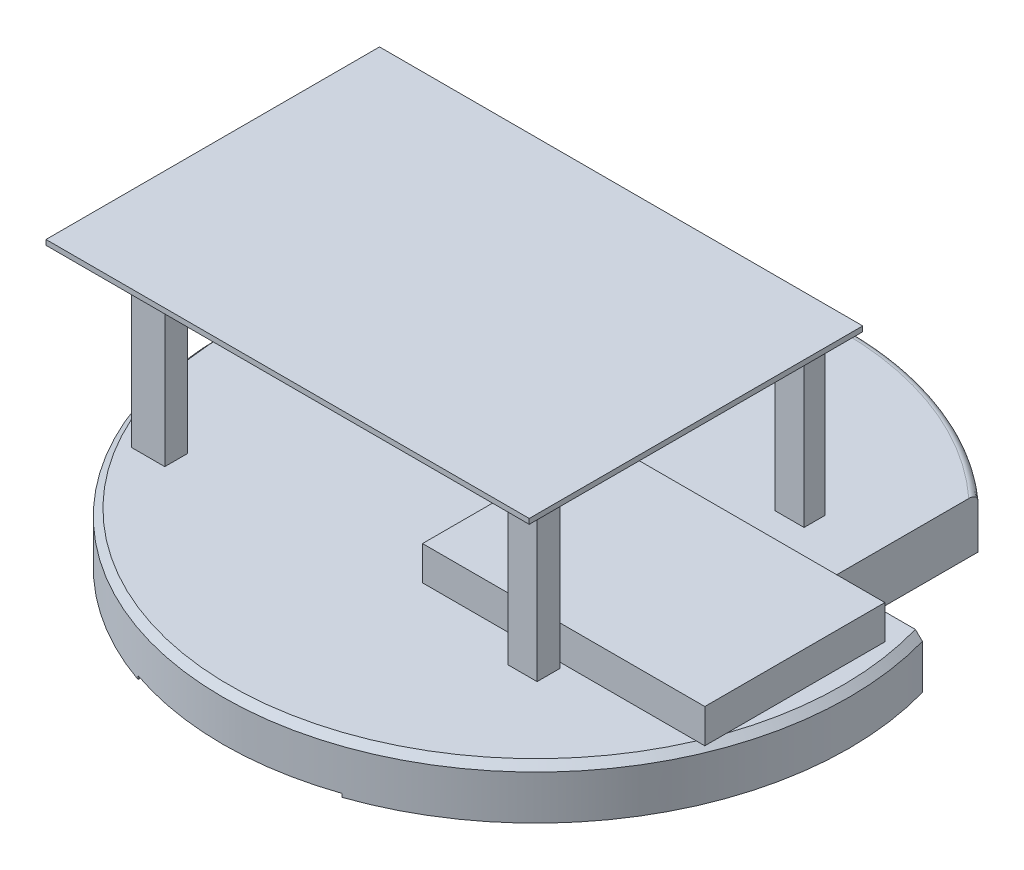
SolidWorks part; units mm, degrees
ref_plane "前视基准面" through (0, 0, 0) normal (0, 0, 1) x (1, 0, 0)
ref_plane "上视基准面" through (0, 0, 0) normal (0, 1, 0) x (1, 0, 0)
ref_plane "右视基准面" through (0, 0, 0) normal (1, 0, 0) x (0, 0, -1)
sketch "草图1" plane through (0, 0, 0) normal (0, 1, 0) x (1, 0, 0)
  line L0 (61, 68.8694) -> (61, 25)
  line L1 (0, 0) -> (0, 6.6219) construction
  line L2 (0, 0) -> (0, 25) construction
  line L3 (61, 25) -> (88.5381, 25)
  line L4 (-61, 25) -> (-88.5381, 25)
  line L5 (-61, 68.8694) -> (-61, 25)
  arc A0 (61, 68.8694) -> (-61, 68.8694) centre (0, 0) ccw
  arc A1 (-88.5381, 25) -> (88.5381, 25) centre (0, 0) ccw
  dimension "D1" = 184
  dimension "D2" = 61
  dimension "D3" = 25
extrude "凸台-拉伸1" add sketch "草图1" along normal blind 15
sketch "草图2" plane through (0, 0, 0) normal (0, -1, 0) x (1, 0, 0)
  line L0 (0, 100.028) -> (0, 25.3301) construction
  line L2 (-30, 49.7832) -> (-30, 92.7832)
  line L3 (-30, 49.7832) -> (30, 49.7832)
  line L4 (30, 49.7832) -> (30, 92.7832)
  line L5 (-30, 92.7832) -> (30, 92.7832)
  line L6 (-30, 49.7832) -> (30, 92.7832) construction
  line L7 (30, 49.7832) -> (-30, 92.7832) construction
  point P3 (0, 71.2832)
  dimension "D1" = 60
  dimension "D2" = 43
extrude "切除-拉伸1" cut sketch "草图2" against normal blind 1
sketch "草图3" plane through (0, 15, 0) normal (0, 1, 0) x (1, 0, 0)
  line L0 (88.5381, 25) -> (61, 25) construction
  line L1 (-93, 47) -> (49, 47)
  line L2 (-93, 47) -> (-93, -51)
  line L3 (-93, -51) -> (49, -51)
  line L4 (49, 47) -> (49, -51)
  line L5 (-93, 47) -> (49, -51) construction
  line L6 (-93, -51) -> (49, 47) construction
  line L7 (61, 25) -> (61, 68.8694) construction
  point P0 (-22, -2)
  dimension "D1" = 142
  dimension "D2" = 98
  dimension "D3" = 22
  dimension "D4" = 12
extrude "凸台-拉伸2" add sketch "草图3" along normal blind 1.5 from offset 46 separate body
sketch "草图4" plane through (0, 15, 0) normal (0, 1, 0) x (1, 0, 0)
  line L1 (35.6001, 40.7083) -> (44.1809, 40.7083)
  line L2 (35.6001, 40.7083) -> (35.6001, 34.5791)
  line L3 (35.6001, 34.5791) -> (44.1809, 34.5791)
  line L4 (44.1809, 40.7083) -> (44.1809, 34.5791)
  line L5 (35.6001, 40.7083) -> (44.1809, 34.5791) construction
  line L6 (35.6001, 34.5791) -> (44.1809, 40.7083) construction
  line L7 (35.6001, -37.1319) -> (44.1809, -37.1319)
  line L8 (35.6001, -37.1319) -> (35.6001, -43.8739)
  line L9 (35.6001, -43.8739) -> (44.1809, -43.8739)
  line L10 (44.1809, -37.1319) -> (44.1809, -43.8739)
  line L11 (35.6001, -37.1319) -> (44.1809, -43.8739) construction
  line L12 (35.6001, -43.8739) -> (44.1809, -37.1319) construction
  line L13 (-75.0309, -37.1319) -> (-65.2243, -37.1319)
  line L14 (-75.0309, -37.1319) -> (-75.0309, -43.8739)
  line L15 (-75.0309, -43.8739) -> (-65.2243, -43.8739)
  line L16 (-65.2243, -37.1319) -> (-65.2243, -43.8739)
  line L17 (-75.0309, -37.1319) -> (-65.2243, -43.8739) construction
  line L18 (-75.0309, -43.8739) -> (-65.2243, -37.1319) construction
  line L19 (-75.0309, 21.6971) -> (-65.2243, 21.6971)
  line L20 (-75.0309, 21.6971) -> (-75.0309, 15.9982)
  line L21 (-75.0309, 15.9982) -> (-65.2243, 15.9982)
  line L22 (-65.2243, 21.6971) -> (-65.2243, 15.9982)
  line L23 (-75.0309, 21.6971) -> (-65.2243, 15.9982) construction
  line L24 (-75.0309, 15.9982) -> (-65.2243, 21.6971) construction
  point P0 (39.8905, 37.6437)
  point P5 (39.8905, -40.5029)
  point P10 (-70.1276, -40.5029)
  point P15 (-70.1276, 18.8477)
extrude "凸台-拉伸3" add sketch "草图4" along normal up to next
chamfer "倒角1" distance 2 angle 45 1 edges at (0, 15, 92)
fillet "圆角1" radius 2 1 edges at (0, 15, -92)
sketch "草图5" plane through (0, 0, 0) normal (0, -1, 0) x (1, 0, 0)
  line L1 (-75.8179, 27.4443) -> (-16.9912, 27.4443)
  line L2 (-75.8179, 27.4443) -> (-75.8179, -13.4145)
  line L3 (-75.8179, -13.4145) -> (-16.9912, -13.4145)
  line L4 (-16.9912, 27.4443) -> (-16.9912, -13.4145)
extrude "凸台-拉伸4" add sketch "草图5" along normal blind 19
sketch "草图6" plane through (0, 15, 0) normal (0, 1, 0) x (1, 0, 0)
  line L1 (85.1557, 17.3527) -> (2.2075, 17.3527)
  line L2 (85.1557, 17.3527) -> (85.1557, -35.5668)
  line L3 (85.1557, -35.5668) -> (2.2075, -35.5668)
  line L4 (2.2075, 17.3527) -> (2.2075, -35.5668)
extrude "凸台-拉伸5" add sketch "草图6" along normal blind 10
